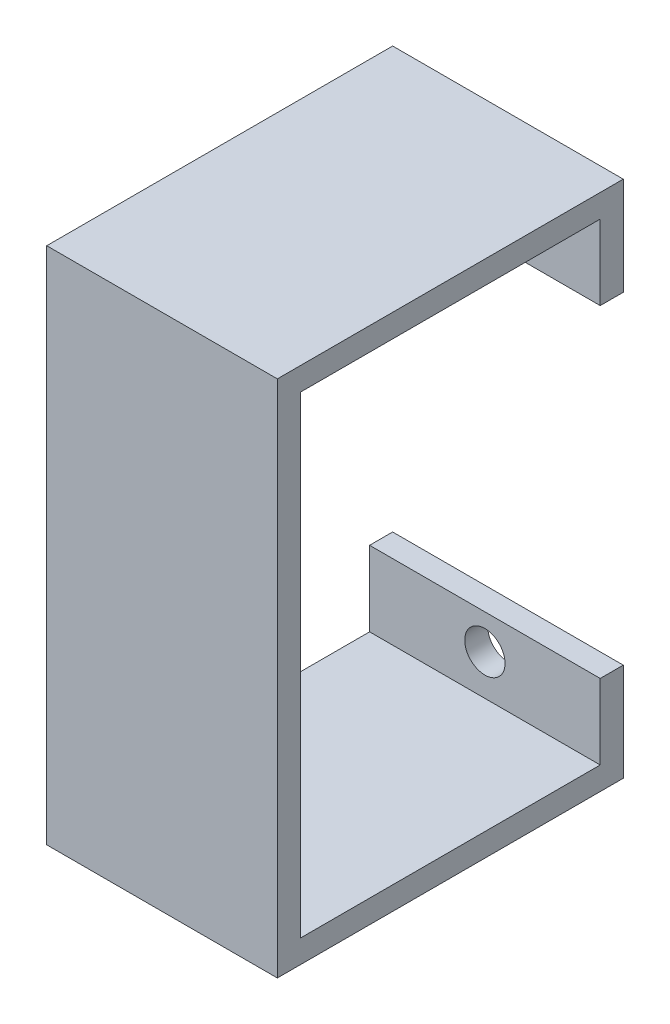
SolidWorks part; units mm, degrees
ref_plane "Top Plane" through (0, 0, 0) normal (0, 0, 1) x (1, 0, 0)
ref_plane "Right Plane" through (0, 0, 0) normal (0, 1, 0) x (1, 0, 0)
ref_plane "Front Plane" through (0, 0, 0) normal (1, 0, 0) x (0, 0, -1)
sketch "Sketch1" plane through (0, 0, 0) normal (1, 0, 0) x (0, 0, -1)
  line L0 (-17.8, -12) -> (0, -12) construction
  line L1 (0, -23) -> (-17.8, -23) construction
  line L2 (0, -23) -> (0, 23) construction
  line L3 (0, 23) -> (-17.8, 23) construction
  line L4 (-17.8, -23) -> (-17.8, 23) construction
  line L5 (-17.8, 12) -> (0, 12) construction
  point P9 (0, 0)
  point P10 (0, 0)
  point P11 (-2.087, -19.4589)
  dimension "D1" = 46
  dimension "D2" = 17.8
  dimension "D3" = 11
  dimension "D4" = 11
sketch "Sketch3" plane through (0, 0, 0) normal (1, 0, 0) x (0, 0, -1)
  line L0 (0, -14) -> (0, -22.5)
  line L1 (0, -23) -> (0, 23) construction
  line L2 (0, -22.5) -> (-30, -22.5)
  line L3 (-30, -22.5) -> (-30, 22.5)
  line L4 (-30, 22.5) -> (0, 22.5)
  line L5 (0, 22.5) -> (0, 14)
  line L6 (-2, -14) -> (-2, -20.5)
  line L7 (-2, -20.5) -> (-28, -20.5)
  line L8 (-28, -20.5) -> (-28, 20.5)
  line L9 (-28, 20.5) -> (-2, 20.5)
  line L10 (-2, 20.5) -> (-2, 14)
  line L11 (-2, -14) -> (0, -14)
  line L12 (0, 22.5) -> (0, 35) construction
  line L13 (2, 20.5) -> (2, 35) construction
  line L14 (-2, 14) -> (0, 14)
  line L15 (-17.8, -12) -> (0, -12) construction
  line L16 (-17.8, 12) -> (0, 12) construction
  line L17 (0, -23) -> (-17.8, -23) construction
  line L18 (0, 23) -> (-17.8, 23) construction
  line L20 (-2, -17) -> (0, -17) construction
  line L21 (-28, 20.5) -> (2, 20.5) construction
  dimension "D1" = 2
  dimension "D2" = 2
  dimension "D3" = 2
  dimension "D4" = 0.5
  dimension "D5" = 0.5
  dimension "D7" = 3
  dimension "D8" = 3.5
  dimension "D10" = 30
extrude "Boss-Extrude1" add sketch "Sketch3" along normal mid plane 20
sketch "Sketch5" plane through (0, 0, 2) normal (0, 0, 1) x (1, 0, 0)
  line L0 (-13.6774, 0) -> (13.9695, 0) construction
  circle A0 centre (0, -17) radius 1.75
  circle A1 centre (0, 17) radius 1.75
  dimension "D1" = 3.5
extrude "Cut-Extrude2" cut sketch "Sketch5" against normal through all
